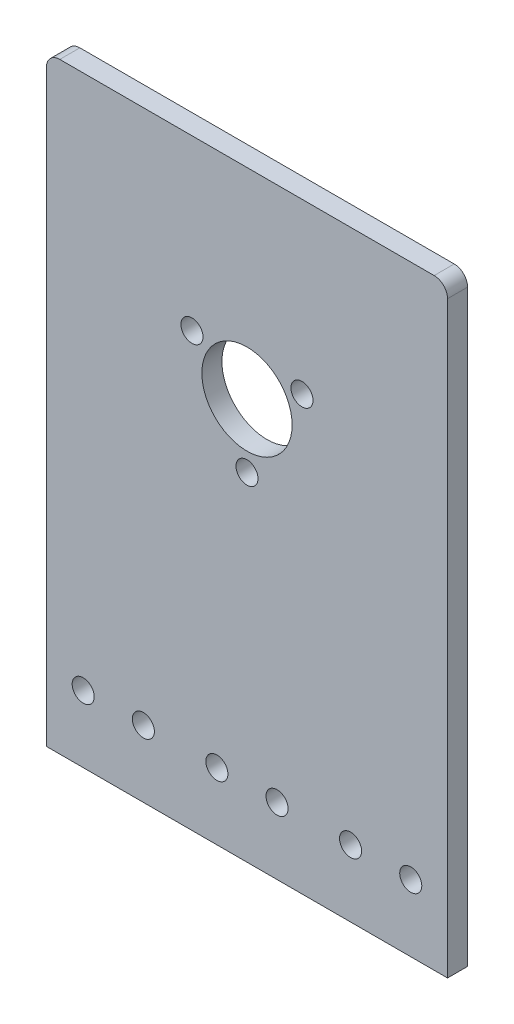
SolidWorks part; units mm, degrees
ref_plane "前视基准面" through (0, 0, 0) normal (0, 0, 1) x (1, 0, 0)
ref_plane "上视基准面" through (0, 0, 0) normal (0, 1, 0) x (1, 0, 0)
ref_plane "右视基准面" through (0, 0, 0) normal (1, 0, 0) x (0, 0, -1)
sketch "草图1" plane through (0, 0, 0) normal (0, 0, 1) x (1, 0, 0)
  line L1 (-30, -45) -> (30, -45)
  line L2 (-30, -45) -> (-30, 45)
  line L3 (-30, 45) -> (30, 45)
  line L4 (30, -45) -> (30, 45)
  line L5 (-30, -45) -> (30, 45) construction
  line L6 (-30, 45) -> (30, -45) construction
  point P0 (0, 0)
  dimension "D1" = 90
  dimension "D2" = 60
extrude "凸台-拉伸1" add sketch "草图1" along normal blind 3
sketch "草图2" plane through (0, 0, 3) normal (0, 0, 1) x (1, 0, 0)
  line L0 (0, 64.4871) -> (0, -56.8412) construction
  line L1 (-30, -45) -> (30, -45) construction
  circle A0 centre (0, 15) radius 9.5 construction
  circle A1 centre (0, 5.5) radius 1.65
  circle A2 centre (-8.2272, 19.75) radius 1.65
  circle A3 centre (8.2272, 19.75) radius 1.65
  dimension "D1" = 60
  dimension "D2" = 19
  dimension "D3" = 3.3
  dimension "D4" = 3
extrude "切除-拉伸1" cut sketch "草图2" against normal blind 3
sketch "草图3" plane through (0, 0, 3) normal (0, 0, 1) x (1, 0, 0)
  line L0 (0, 19.1236) -> (0, -38.6111) construction
  line L1 (-4.5, -35) -> (4.5, -35) construction
  line L2 (-30, -45) -> (30, -45) construction
  line L3 (-30, -35) -> (30, -35) construction
  line L4 (-30, 45) -> (-30, -45) construction
  line L5 (30, -45) -> (30, 45) construction
  circle A0 centre (4.5, -35) radius 1.65
  circle A1 centre (-4.5, -35) radius 1.65
  circle A4 centre (24.5, -35) radius 1.65
  circle A5 centre (15.5, -35) radius 1.65
  circle A6 centre (-24.5, -35) radius 1.65
  circle A7 centre (-15.5, -35) radius 1.65
  dimension "D1" = 3.3
  dimension "D2" = 3.3
  dimension "D4" = 4.5
  dimension "D5" = 4.5
  dimension "D12" = 3.3
  dimension "D13" = 3.3
  dimension "D14" = 9
  dimension "D16" = 3.3
  dimension "D17" = 3.3
  dimension "D18" = 9
  dimension "D6" = 5.5
  dimension "D7" = 5.5
  dimension "D3" = 10
  dimension "D8" = 10
extrude "切除-拉伸2" cut sketch "草图3" against normal blind 3
sketch "草图4" plane through (0, 0, 3) normal (0, 0, 1) x (1, 0, 0)
  circle A0 centre (0, 15) radius 6.75
  dimension "D1" = 13.5
extrude "切除-拉伸3" cut sketch "草图4" against normal blind 3
fillet "圆角1" radius 2 2 edges at (30, 45, 1.5) (-30, 45, 1.5)
